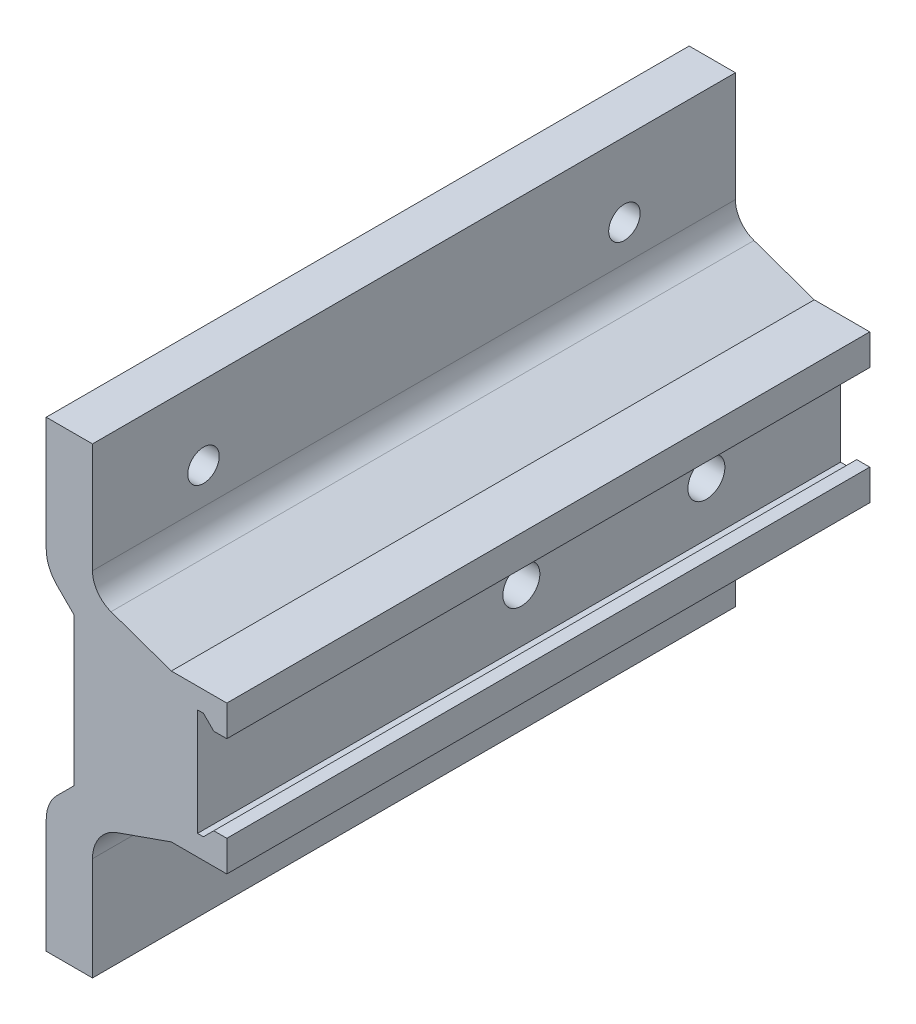
SolidWorks part; units mm, degrees
ref_plane "Front Plane" through (0, 0, 0) normal (0, 0, 1) x (1, 0, 0)
ref_plane "Top Plane" through (0, 0, 0) normal (0, 1, 0) x (1, 0, 0)
ref_plane "Right Plane" through (0, 0, 0) normal (1, 0, 0) x (0, 0, -1)
sketch "Sketch4" plane through (0, 0, 0) normal (0, 0, 1) x (1, 0, 0)
  line L1 (-4.3026, 10.3735) -> (-10.3026, 10.3735)
  line L2 (-6.8326, 8.1535) -> (-5.7126, 7.0335)
  line L3 (-7.4626, 8.1535) -> (-7.4626, -3.4065)
  line L4 (-6.8326, 8.1535) -> (-7.4626, 8.1535)
  line L5 (-13.1609, 2.3735) -> (1.8792, 2.3735) construction
  line L6 (-10.3026, 10.3735) -> (-10.3026, -5.6265)
  line L7 (-4.3026, 7.0335) -> (-4.3026, 10.3735)
  line L8 (-4.3026, -2.2865) -> (-4.3026, -5.6265)
  line L9 (-6.8326, -3.4065) -> (-7.4626, -3.4065)
  line L10 (-6.8326, -3.4065) -> (-5.7126, -2.2865)
  line L11 (-4.3026, -5.6265) -> (-10.3026, -5.6265)
  line L13 (-5.7126, 7.0335) -> (-4.3026, 7.0335)
  line L14 (-5.7126, -2.2865) -> (-4.3026, -2.2865)
  point P13 (-10.3026, 2.3735)
  point P15 (-7.4626, 2.3735)
  dimension "D1" = 1.12
  dimension "D2" = 1.12
  dimension "D3" = 1.12
  dimension "D4" = 0.63
  dimension "D5" = 5.78
  dimension "D6" = 2.53
  dimension "D7" = 16
  dimension "D8" = 1.12
extrude "Boss-Extrude2" add sketch "Sketch4" along normal blind 69.5
sketch "Sketch6" plane through (0, 0, 69.5) normal (0, 0, 1) x (1, 0, 0)
  line L0 (-7.4626, 2.3735) -> (-26.1204, 2.3735) construction
  line L1 (-7.4626, -3.4065) -> (-7.4626, 8.1535) construction
  line L2 (-18.8238, 27.3735) -> (-23.8238, 27.3735)
  line L3 (-23.8238, 27.3735) -> (-23.8238, 15.0303)
  line L4 (-10.3026, 10.3735) -> (-10.3026, -5.6265)
  line L5 (-10.3026, 10.3735) -> (-10.3026, -5.6265) construction
  line L6 (-18.8238, -22.6265) -> (-23.8238, -22.6265)
  line L7 (-18.8238, 27.3735) -> (-18.8238, 15.4978)
  line L8 (-16.82, 12.668) -> (-10.3026, 10.3735)
  line L9 (-16.1521, -7.6859) -> (-10.3026, -5.6265)
  line L10 (-18.8238, -22.6265) -> (-18.8238, -11.4589)
  line L11 (-22.6522, 12.2019) -> (-20.8238, 10.3735)
  line L12 (-20.8238, 10.3735) -> (-20.8238, -5.6265)
  line L13 (-20.8238, -5.6265) -> (-22.6522, -7.455)
  line L14 (-23.8238, -10.2834) -> (-23.8238, -22.6265)
  arc A1 (-16.82, 12.668) -> (-18.8238, 15.4978) centre (-15.8238, 15.4978) cw
  arc A2 (-18.8238, -11.4589) -> (-16.1521, -7.6859) centre (-14.8238, -11.4589) cw
  arc A3 (-22.6522, 12.2019) -> (-23.8238, 15.0303) centre (-19.8238, 15.0303) cw
  arc A4 (-23.8238, -10.2834) -> (-22.6522, -7.455) centre (-19.8238, -10.2834) cw
  point P16 (-10.3026, 2.3735)
  point P17 (-23.8238, 2.3735)
  point P23 (-18.8238, 13.3735)
  point P26 (-18.8238, -8.6265)
  point P31 (-23.8238, -8.6265)
  dimension "D1" = 14
  dimension "D6" = 3
  dimension "D7" = 4
  dimension "D8" = 4
  dimension "D9" = 4
  dimension "D2" = 50
  dimension "D3" = 5
  dimension "D4" = 3
  dimension "D5" = 16
extrude "Boss-Extrude3" add sketch "Sketch6" against normal up to surface (69.5 mm away) up to face at (-6.4859, 2.3735, 0)
sketch "Sketch7" plane through (-7.4626, 0, 0) normal (1, 0, 0) x (0, 0, -1)
  line L0 (-69.5, 2.3735) -> (0, 2.3735) construction
  line L1 (-69.5, -3.4065) -> (-69.5, 8.1535) construction
  line L2 (0, -3.4065) -> (0, 8.1535) construction
  circle A0 centre (-34.5, 2.3735) radius 2
  circle A1 centre (-14.5, 2.3735) radius 2
  dimension "D1" = 4
  dimension "D2" = 4
  dimension "D3" = 35
  dimension "D4" = 55
extrude "Cut-Extrude1" cut sketch "Sketch7" against normal through all and the other way through all
sketch "Sketch8" plane through (-23.8238, 0, 0) normal (-1, 0, 0) x (0, 0, 1)
  line L0 (0, 2.3735) -> (69.5, 2.3735) construction
  line L1 (0, 27.3735) -> (0, 15.0303) construction
  line L2 (69.5, 27.3735) -> (69.5, 15.0303) construction
  line L3 (0, 27.3735) -> (69.5, 27.3735) construction
  line L4 (0, 10.3735) -> (0, -5.6265) construction
  line L5 (69.5, 10.3735) -> (69.5, -5.6265) construction
  circle A0 centre (12, 19.3735) radius 1.7
  circle A1 centre (57.5, 19.3735) radius 1.7
  circle A4 centre (57.5, -14.6265) radius 1.7
  circle A5 centre (12, -14.6265) radius 1.7
  dimension "D1" = 3.4
  dimension "D2" = 3.4
  dimension "D3" = 12
  dimension "D4" = 12
  dimension "D5" = 8
  dimension "D6" = 8
extrude "Cut-Extrude2" cut sketch "Sketch8" against normal through all and the other way through all
